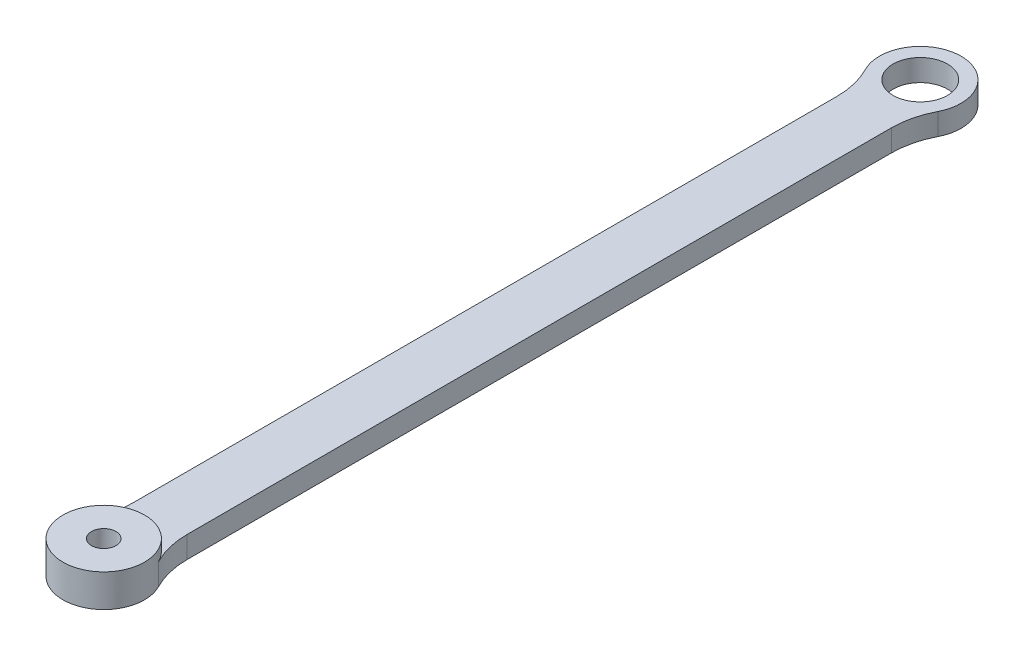
SolidWorks part; units mm, degrees
ref_plane "Front Plane" through (0, 0, 0) normal (0, 0, 1) x (1, 0, 0)
ref_plane "Top Plane" through (0, 0, 0) normal (0, 1, 0) x (1, 0, 0)
ref_plane "Right Plane" through (0, 0, 0) normal (1, 0, 0) x (0, 0, -1)
sketch "Sketch1" plane through (0, 0, 0) normal (0, 1, 0) x (1, 0, 0)
  line L1 (-5, -75) -> (5, -75)
  line L2 (-5, -75) -> (-5, 75)
  line L3 (-5, 75) -> (5, 75)
  line L4 (5, -75) -> (5, 75)
  line L5 (-5, -75) -> (5, 75) construction
  line L6 (-5, 75) -> (5, -75) construction
  circle A0 centre (0, 75) radius 5
  circle A1 centre (0, -75) radius 2.25
  circle A2 centre (0, 75) radius 7.5
  circle A3 centre (0, -75) radius 7.5
  point P0 (0, 0)
  dimension "D2" = 15
  dimension "D3" = 15
  dimension "D5" = 4.5
  dimension "D1" = 150
  dimension "D4" = 10
extrude "Boss-Extrude1" add sketch "Sketch1" along normal blind 4 contours L2 A3 L4 A1 | L4 A3 L2 A1 | A3 L4 A2 L2 | L3 A0 | L3 A0
fillet "Fillet1" radius 15 4 edges at (-5, 2, -69.4098) (5, 2, -69.4098) (5, 2, 69.4098) (-5, 2, 69.4098)
sketch "Sketch2" plane through (0, 4, 0) normal (0, 1, 0) x (1, 0, 0)
  circle A0 centre (0, -75) radius 7.5
  circle A1 centre (0, -75) radius 2.25
extrude "Boss-Extrude2" add sketch "Sketch2" along normal blind 2
